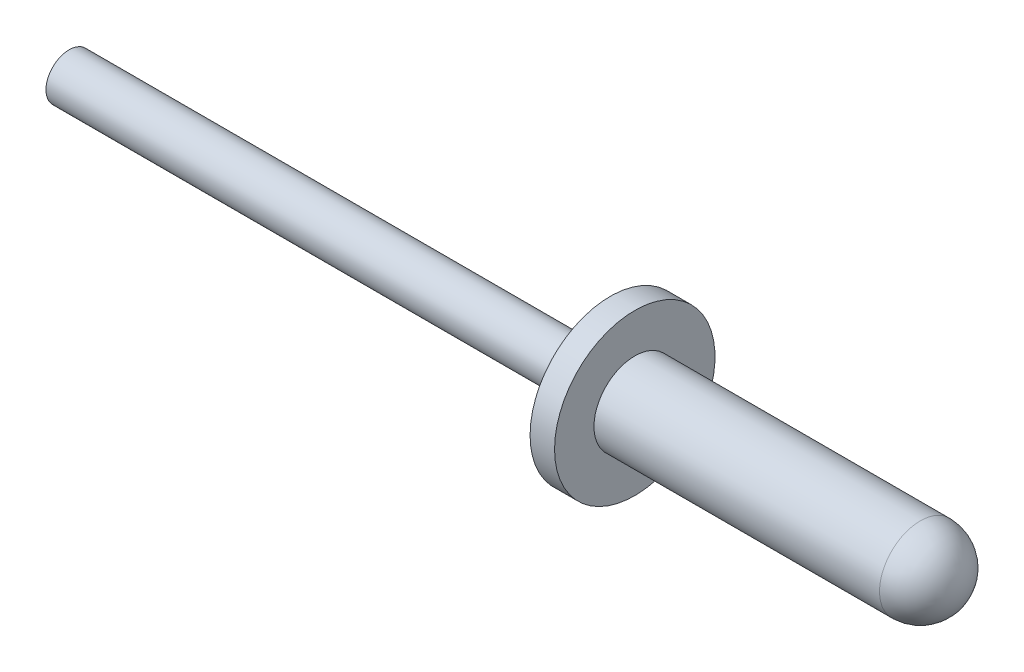
SolidWorks part; units mm, degrees
ref_plane "Front Plane" through (0, 0, 0) normal (0, 0, 1) x (1, 0, 0)
ref_plane "Top Plane" through (0, 0, 0) normal (0, 1, 0) x (1, 0, 0)
ref_plane "Right Plane" through (0, 0, 0) normal (1, 0, 0) x (0, 0, -1)
sketch "Sketch1" plane through (0, 0, 0) normal (1, 0, 0) x (0, 0, -1)
  circle A0 centre (0, 0) radius 1.5
  dimension "D1" = 3
extrude "Boss-Extrude1" add sketch "Sketch1" along normal blind 10.5
sketch "Sketch8" plane through (10.5, 0, 0) normal (1, 0, 0) x (0, 0, -1)
  line L0 (1.5, 0) -> (-1.5, 0)
  circle A1 centre (0, 0) radius 1.5
  arc A2 (1.5, 0) -> (-1.5, 0) centre (0, 0) ccw
  dimension "D1" = 0
revolve "Revolve1" add sketch "Sketch8" angle 360 about L0
sketch "Sketch2" plane through (0, 0, 0) normal (-1, 0, 0) x (0, 0, 1)
  circle A0 centre (0, 0) radius 2.95
  dimension "D1" = 5.9
extrude "Boss-Extrude2" add sketch "Sketch2" along normal blind 0.9 contours A0
sketch "Sketch3" plane through (0, 0, 0) normal (0, 0, 1) x (1, 0, 0)
  line L0 (-0.9, 0) -> (-20.8, 0)
  line L1 (-0.9, 2.95) -> (-0.9, -2.95) construction
  dimension "D3" = 19.9
sweep "Sweep1" add path "Sketch3" circular profile diameter 1.7 parameters "D3"=1.7
